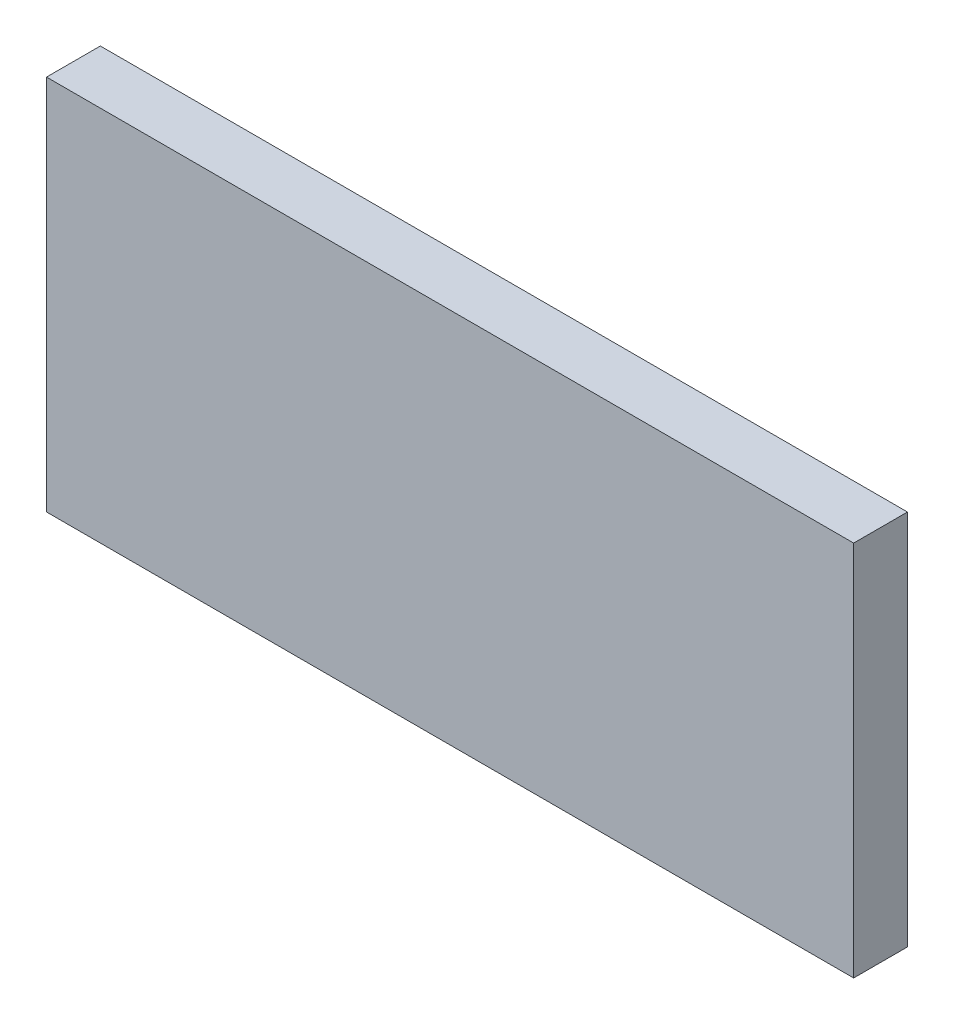
SolidWorks part; units mm, degrees
ref_plane "Plan de face" through (0, 0, 0) normal (0, 0, 1) x (1, 0, 0)
ref_plane "Plan de dessus" through (0, 0, 0) normal (0, 1, 0) x (1, 0, 0)
ref_plane "Plan de droite" through (0, 0, 0) normal (1, 0, 0) x (0, 0, -1)
sketch "Esquisse1" plane through (0, 0, 0) normal (0, 0, 1) x (1, 0, 0)
  line L1 (0, 0) -> (150, 0)
  line L2 (0, 0) -> (0, 70)
  line L3 (0, 70) -> (150, 70)
  line L4 (150, 0) -> (150, 70)
  dimension "D1" = 70
  dimension "D2" = 150
extrude "Boss.-Extru.1" add sketch "Esquisse1" along normal blind 10
